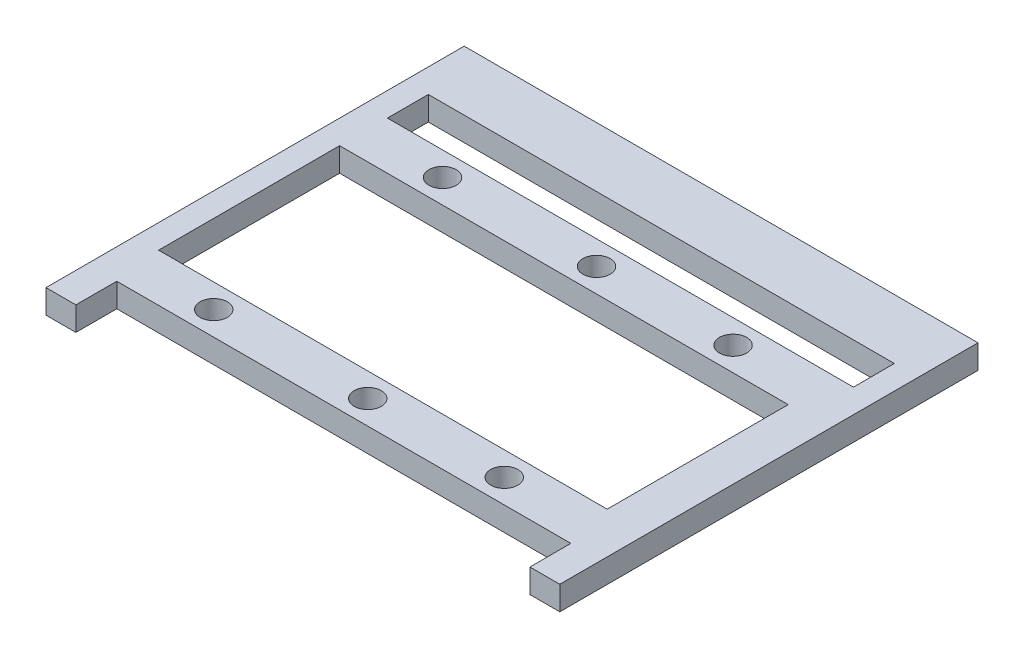
SolidWorks part; units mm, degrees
ref_plane "Front Plane" through (0, 0, 0) normal (0, 0, 1) x (1, 0, 0)
ref_plane "Top Plane" through (0, 0, 0) normal (0, 1, 0) x (1, 0, 0)
ref_plane "Right Plane" through (0, 0, 0) normal (1, 0, 0) x (0, 0, -1)
sketch "Sketch2" plane through (0, 0, 0) normal (0, 1, 0) x (1, 0, 0)
  line L5 (43, 30) -> (39, 30)
  line L6 (-43, -30) -> (-21.715, -15.15) construction
  line L10 (36.0793, 0) -> (41.5621, 0) construction
  line L11 (-39, 0) -> (-43, 0) construction
  line L12 (-39, 23.15) -> (39, 23.15)
  line L14 (36.0793, 15.15) -> (-39, 15.15)
  line L16 (36.0793, -15.15) -> (-39, -15.15)
  line L18 (-38, -23.15) -> (38, -23.15)
  line L20 (-39, 15.15) -> (-39, -15.15)
  line L21 (-39, 23.15) -> (-39, 30)
  line L24 (36.0793, 15.15) -> (36.0793, -15.15)
  line L25 (39, 30) -> (39, 23.15)
  line L27 (-43, 30) -> (-43, -30)
  line L28 (-43, -30) -> (-38, -30)
  line L30 (-38, -30) -> (-38, -23.15)
  line L33 (-43, 30) -> (-39, 30)
  line L34 (21.715, -15.15) -> (43, -30) construction
  line L35 (43, 30) -> (43, -30)
  line L36 (38, -23.15) -> (38, -30)
  line L37 (38, -30) -> (43, -30)
  circle A0 centre (-25.775, 19.15) radius 2.275
  circle A1 centre (22.8543, 19.15) radius 2.275
  circle A2 centre (0, 19.15) radius 2.275
  circle A3 centre (22.8543, -19.15) radius 2.275
  circle A4 centre (0, -19.15) radius 2.275
  circle A5 centre (-25.775, -19.15) radius 2.275
  point P0 (0, 0)
  point P6 (0, 0)
  dimension "D3" = 4.55
  dimension "D4" = 4.55
  dimension "D5" = 4.55
  dimension "D1" = 86
  dimension "D2" = 60
  dimension "D6" = 19.15
  dimension "D7" = 19.15
  dimension "D8" = 38.3
  dimension "D9" = 4
  dimension "D10" = 4
  dimension "D11" = 13.225
  dimension "D12" = 12.225
  dimension "D13" = 13.225
  dimension "D14" = 43
extrude "Boss-Extrude1" add sketch "Sketch2" along normal blind 4
sketch "Sketch3" plane through (0, 0, -30) normal (0, 0, -1) x (-1, 0, 0)
  line L1 (-43, 0) -> (43, 0)
  line L2 (-43, 0) -> (-43, 4)
  line L3 (-43, 4) -> (43, 4)
  line L4 (43, 0) -> (43, 4)
extrude "Boss-Extrude2" add sketch "Sketch3" along normal blind 10
